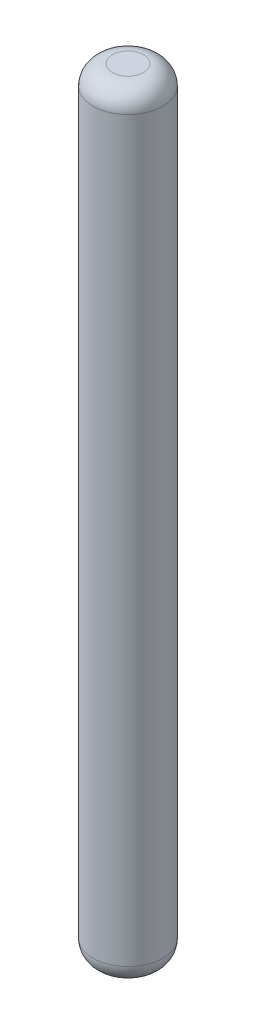
SolidWorks part; units mm, degrees
ref_plane "Front Plane" through (0, 0, 0) normal (0, 0, 1) x (1, 0, 0)
ref_plane "Top Plane" through (0, 0, 0) normal (0, 1, 0) x (1, 0, 0)
ref_plane "Right Plane" through (0, 0, 0) normal (1, 0, 0) x (0, 0, -1)
sketch "Sketch1" plane through (0, 0, 0) normal (0, 1, 0) x (1, 0, 0)
  circle A0 centre (0, 0) radius 1.143
  dimension "D1" = 2.286
extrude "Boss-Extrude1" add sketch "Sketch1" along normal blind 25.4
fillet "Fillet2" radius 0.635 2 edges at (0, 0, 1.143) (0, 25.4, 1.143)
